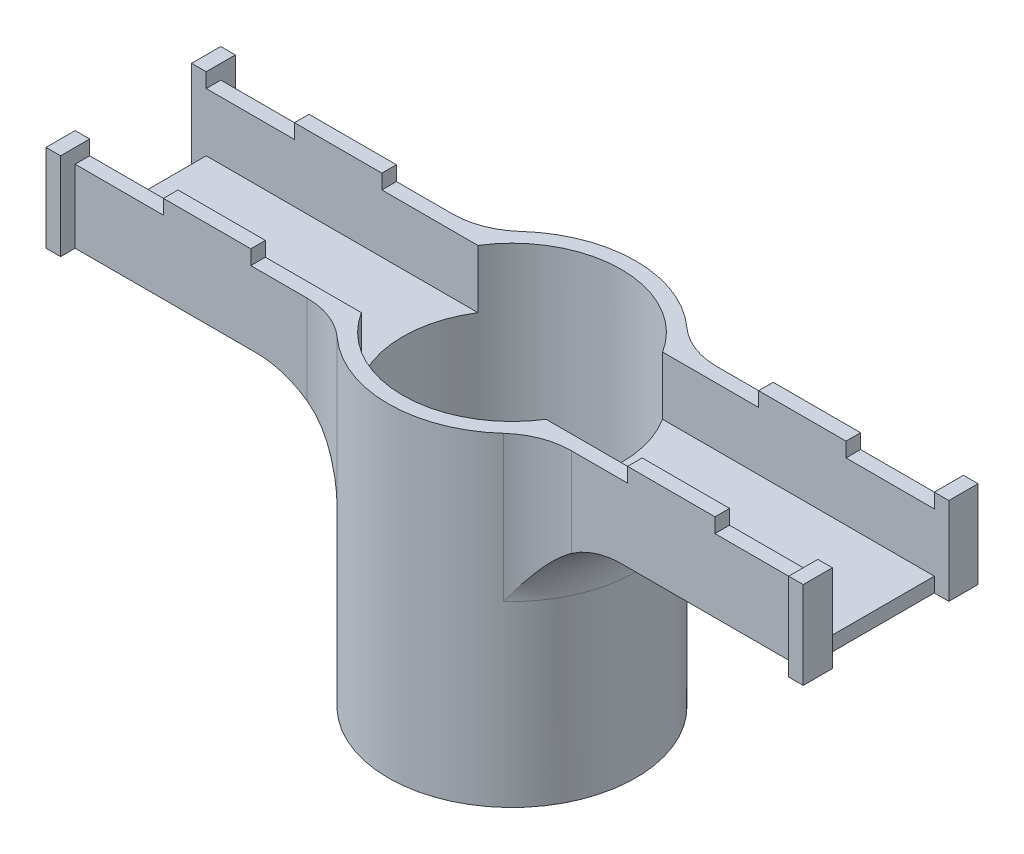
SolidWorks part; units mm, degrees
ref_plane "前视基准面" through (0, 0, 0) normal (0, 0, 1) x (1, 0, 0)
ref_plane "上视基准面" through (0, 0, 0) normal (0, 1, 0) x (1, 0, 0)
ref_plane "右视基准面" through (0, 0, 0) normal (1, 0, 0) x (0, 0, -1)
sketch "草图1" plane through (0, 0, 0) normal (0, 1, 0) x (1, 0, 0)
  line L0 (-22.0878, 0) -> (22.0878, 0) construction
  line L1 (6.7175, 6.7175) -> (0, 0) construction
  circle A0 centre (0, 0) radius 17
  circle A1 centre (0, 0) radius 7
  circle A2 centre (0, 0) radius 9.5 construction
  circle A3 centre (6.7175, 6.7175) radius 1.6
  circle A4 centre (2.4588, -9.1763) radius 1.6
  circle A5 centre (-9.1763, 2.4588) radius 1.6
  point P9 (0, 0)
  point P17 (0, 0)
  dimension "D1" = 34
  dimension "D2" = 14
  dimension "D3" = 19
  dimension "D4" = 3.2
  dimension "D5" = 45
  dimension "D6" = 3
extrude "凸台-拉伸1" add sketch "草图1" against normal blind 2
sketch "草图2" plane through (0, 0, 0) normal (0, 1, 0) x (1, 0, 0)
  circle A2 centre (0, 0) radius 15
  circle A3 centre (0, 0) radius 17
  dimension "D1" = 30
  dimension "D2" = 2
extrude "凸台-拉伸2" add sketch "草图2" along normal blind 42.5
ref_plane "基准面1" through (50, 0, 0) normal (1, 0, 0) x (0, 0, -1)
sketch "草图4" plane through (50, 0, 0) normal (1, 0, 0) x (0, 0, -1)
  line L0 (-10, 42.5) -> (-8, 42.5)
  line L1 (-8, 42.5) -> (-8, 34.5)
  line L2 (-8, 34.5) -> (8, 34.5)
  line L3 (8, 34.5) -> (8, 42.5)
  line L4 (8, 42.5) -> (10, 42.5)
  line L5 (10, 42.5) -> (10, 32.5)
  line L6 (10, 32.5) -> (-10, 32.5)
  line L7 (-10, 32.5) -> (-10, 42.5)
  line L8 (0, 17.6029) -> (0, 47.2393) construction
  line L10 (17, 42.5) -> (-17, 42.5) construction
  point P11 (0, 34.5)
  dimension "D1" = 2
  dimension "D2" = 2
  dimension "D4" = 16
  dimension "D5" = 8
  dimension "D3" = 2
extrude "凸台-拉伸3" add sketch "草图4" against normal up to next
sketch "草图5" plane through (50, 0, 0) normal (1, 0, 0) x (0, 0, -1)
  line L0 (-10, 32.5) -> (10, 32.5) construction
  line L1 (-8, 44.5) -> (-12, 44.5)
  line L2 (-8, 44.5) -> (-8, 32.5)
  line L3 (-8, 32.5) -> (-12, 32.5)
  line L4 (-12, 44.5) -> (-12, 32.5)
  line L5 (-10, 32.5) -> (10, 32.5) construction
  line L6 (8, 44.5) -> (12, 44.5)
  line L7 (8, 44.5) -> (8, 32.5)
  line L8 (8, 32.5) -> (12, 32.5)
  line L9 (12, 44.5) -> (12, 32.5)
  line L10 (-8, 34.5) -> (-8, 42.5) construction
  line L11 (-8, 42.5) -> (-10, 42.5) construction
  line L12 (8, 42.5) -> (8, 34.5) construction
  line L13 (10, 42.5) -> (8, 42.5) construction
  point P5 (-8.6143, 45.3953)
  point P15 (-8.4266, 32.5)
  dimension "D1" = 4
  dimension "D2" = 4
  dimension "D3" = 2
  dimension "D4" = 2
extrude "凸台-拉伸4" add sketch "草图5" along normal blind 2
sketch "草图6" plane through (50, 0, 0) normal (1, 0, 0) x (0, 0, -1)
  line L1 (-8, 42.5) -> (8, 42.5)
  line L2 (-8, 42.5) -> (-8, 34.5)
  line L3 (-8, 34.5) -> (8, 34.5)
  line L4 (8, 42.5) -> (8, 34.5)
  point P6 (-8, 42.5)
extrude "切除-拉伸1" cut sketch "草图6" against normal up to next
sketch "草图7" plane through (0, 42.5, 0) normal (0, 1, 0) x (1, 0, 0)
  line L0 (12.6886, -8) -> (50, -8) construction
  line L1 (25.8739, -8) -> (37.8739, -8)
  line L2 (25.8739, -8) -> (25.8739, -10)
  line L3 (25.8739, -10) -> (37.8739, -10)
  line L4 (37.8739, -8) -> (37.8739, -10)
  line L5 (13.7477, -10) -> (50, -10) construction
  line L6 (31.8739, -10) -> (31.8739, -1.2949) construction
  point P13 (31.8739, -10)
  dimension "D1" = 12
extrude "凸台-拉伸5" add sketch "草图7" along normal blind 2
mirror "镜向1" about plane through (0, 0, 0) normal (0, 0, 1) of "凸台-拉伸5"
mirror "镜向2" about plane through (0, 0, 0) normal (1, 0, 0) of "镜向1", "切除-拉伸1", "凸台-拉伸4", "凸台-拉伸3"
fillet "圆角1" radius 10 6 edges at (-17, 32.5, 0) (17, 32.5, 0) (-13.7477, 37.5, -10) (13.7477, 37.5, -10) (13.7477, 37.5, 10) (-13.7477, 37.5, 10)
equation "\"拨盘中径\"= 64'8ball"
equation "\"球通道直径\"= 18"
equation "\"壁厚\"=2"
equation "\"加强筋高\"= 4"
equation "\"M3螺丝孔\"= 3.2"
equation "\"M3沉头孔\"= 6.5'杯头螺钉头高3mm"
equation "\"M3螺母孔\"= 6"
equation "\"电机杯直径\"= 30"
equation "\"D1@草图1\"=\"电机杯直径\"+\"壁厚\"*2"
equation "\"D4@草图1\"=\"M3螺丝孔\""
equation "\"D1@凸台-拉伸1\"=\"壁厚\""
equation "\"D1@草图2\"=\"电机杯直径\""
equation "\"D2@草图2\"=\"壁厚\""
equation "\"线槽宽\"= 16"
equation "\"线槽高\"= 8"
equation "\"D1@草图4\"=\"壁厚\""
equation "\"D2@草图4\"=\"壁厚\""
equation "\"D4@草图4\"=\"线槽宽\""
equation "\"D5@草图4\"=\"线槽高\""
equation "\"D3@草图4\"=\"壁厚\""
equation "\"D1@草图5\"=\"壁厚\"*2"
equation "\"D2@草图5\"= \"壁厚\" *2"
equation "\"D1@凸台-拉伸4\"=\"壁厚\""
equation "\"D1@凸台-拉伸5\"=\"壁厚\""
equation "\"D3@草图5\"=\"壁厚\""
equation "\"D4@草图5\"=\"壁厚\""
